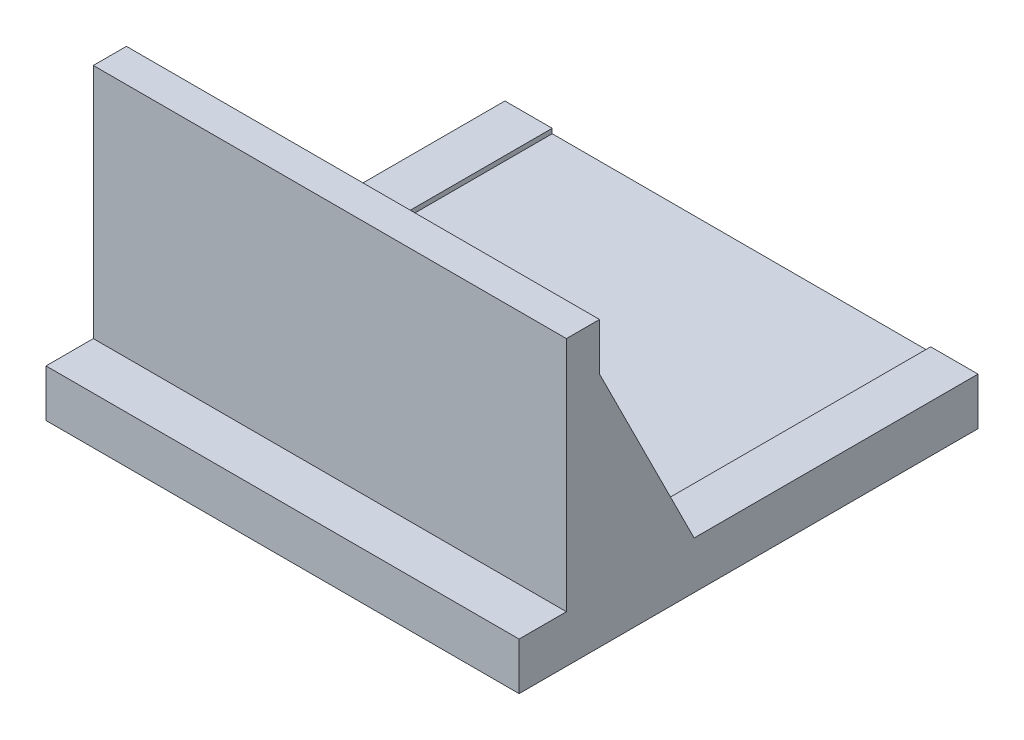
SolidWorks part; units mm, degrees
ref_plane "前视基准面" through (0, 0, 0) normal (0, 0, 1) x (1, 0, 0)
ref_plane "上视基准面" through (0, 0, 0) normal (0, 1, 0) x (1, 0, 0)
ref_plane "右视基准面" through (0, 0, 0) normal (1, 0, 0) x (0, 0, -1)
other "Configuration Table"
sketch "草图1" plane through (0, 0, 0) normal (0, 0, 1) x (1, 0, 0)
  line L1 (-50, -30) -> (50, -30)
  line L2 (-50, -30) -> (-50, 30)
  line L3 (-50, 30) -> (50, 30)
  line L4 (50, -30) -> (50, 30)
  line L5 (-50, -30) -> (50, 30) construction
  line L6 (-50, 30) -> (50, -30) construction
  point P0 (0, 0)
  dimension "D1" = 100
  dimension "D2" = 60
extrude "凸台-拉伸1" add sketch "草图1" along normal blind 37
sketch "草图2" plane through (50, 0, 0) normal (1, 0, 0) x (0, 0, -1)
  line L1 (-37, 30) -> (-27, 30)
  line L2 (-37, 30) -> (-37, -20)
  line L3 (-37, -20) -> (-27, -20)
  line L4 (-27, 30) -> (-27, -20)
  line L5 (-37, -30) -> (0, -30) construction
  dimension "D1" = 10
  dimension "D2" = 10
extrude "切除-拉伸1" cut sketch "草图2" against normal through all
sketch "草图3" plane through (0, 30, 0) normal (0, 1, 0) x (1, 0, 0)
  line L0 (50, 0) -> (-50, 0) construction
  line L1 (-40, 0) -> (40, 0)
  line L2 (-40, 0) -> (-40, -20)
  line L3 (-40, -20) -> (40, -20)
  line L4 (40, 0) -> (40, -20)
  line L5 (-50, -27) -> (-50, 0) construction
  line L6 (50, -27) -> (50, 0) construction
  dimension "D1" = 10
  dimension "D2" = 10
  dimension "D3" = 20
extrude "切除-拉伸2" cut sketch "草图3" against normal blind 50
sketch "草图4" plane through (50, 0, 0) normal (1, 0, 0) x (0, 0, -1)
  line L0 (-20, 30) -> (-20, -30)
  line L1 (-27, 30) -> (0, 30) construction
  line L2 (-37, -30) -> (0, -30) construction
  line L3 (0, -20) -> (-20, 20)
  line L4 (-27, -20) -> (-27, 30) construction
  line L5 (-20, 30) -> (0, 30)
  line L6 (0, 30) -> (0, -20)
  line M4 (0, 30) -> (-27, 30)
  line M9 (0, -30) -> (0, 30)
  dimension "D1" = 7
  dimension "D2" = 10
extrude "切除-拉伸3" cut sketch "草图4" against normal through all contours L3 L0 M9 M4
sketch "草图5" plane through (0, -20, 0) normal (0, 1, 0) x (1, 0, 0)
  line L1 (-40, 0) -> (40, 0)
  line L2 (-40, 0) -> (-40, -20)
  line L3 (-40, -20) -> (40, -20)
  line L4 (40, 0) -> (40, -20)
extrude "切除-拉伸4" cut sketch "草图5" against normal blind 1
sketch "草图7" plane through (0, 0, 0) normal (0, 0, -1) x (-1, 0, 0)
  line L0 (-50, -20) -> (-40, -20)
  line L1 (40, -20) -> (50, -20)
  line L2 (50, -30) -> (-50, -30)
  line L3 (50, -20) -> (50, -30) construction
  line L4 (50, -30) -> (-50, -30) construction
  line L5 (-50, -20) -> (-50, -30)
  line L6 (-40, -20) -> (-40, -21)
  line L7 (40, -20) -> (40, -21)
  line L8 (50, -20) -> (50, -30)
  line L17 (40, -20) -> (40, -21)
  line L18 (40, -21) -> (-40, -21)
  line L19 (-40, -21) -> (-40, -20)
  line L20 (-40, -20) -> (-50, -20)
  line L21 (-50, -20) -> (-50, -30)
  line L22 (-50, -30) -> (50, -30)
  line L23 (50, -30) -> (50, -20)
  line L24 (50, -20) -> (40, -20)
  line L25 (40, -20) -> (40, -21)
  line L27 (-40, -21) -> (-40, -20)
  line L28 (-40, -20) -> (-50, -20)
  line L29 (-50, -20) -> (-50, -30)
  line L30 (-50, -30) -> (50, -30)
  line L31 (50, -30) -> (50, -20)
  line L32 (50, -20) -> (40, -20)
  line M16 (40, -20) -> (40, -21)
  line M17 (40, -21) -> (-40, -21)
  line M18 (-40, -21) -> (-40, -20)
  line M19 (-40, -20) -> (-50, -20)
  line M20 (-50, -20) -> (-50, -30)
  line M21 (-50, -30) -> (50, -30)
  line M22 (50, -30) -> (50, -20)
  line M23 (50, -20) -> (40, -20)
  dimension "D1" = 0
extrude "凸台-拉伸2" add sketch "草图7" along normal blind 60 contours M23 M16 M17 M18 M19 M20 M21 M22
